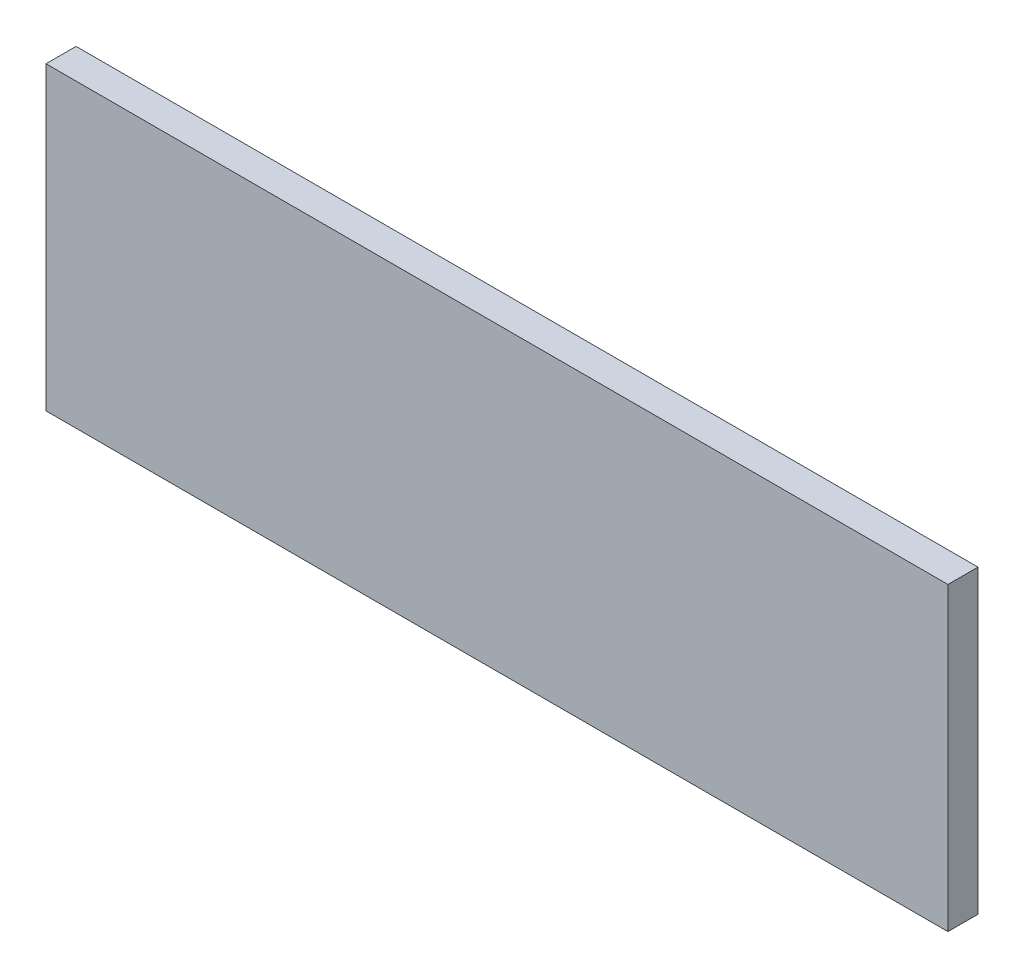
SolidWorks part; units mm, degrees
material "Простая углеродистая сталь"
ref_plane "Спереди" through (0, 0, 0) normal (0, 0, 1) x (1, 0, 0)
ref_plane "Сверху" through (0, 0, 0) normal (0, 1, 0) x (1, 0, 0)
ref_plane "Справа" through (0, 0, 0) normal (1, 0, 0) x (0, 0, -1)
sketch "Эскиз1" plane through (0, 0, 0) normal (0, 0, 1) x (1, 0, 0)
  line L1 (0, 0) -> (3000, 0)
  line L2 (0, 0) -> (0, -1000)
  line L3 (0, -1000) -> (3000, -1000)
  line L4 (3000, 0) -> (3000, -1000)
  line L5 (1500, -1000) -> (1500, 0) construction
  line L6 (0, -500) -> (3000, -500) construction
  point P88 (1500, -500)
  dimension "D1" = 3000
  dimension "D2" = 1000
extrude "Бобышка-Вытянуть1" add sketch "Эскиз1" along normal blind 100
